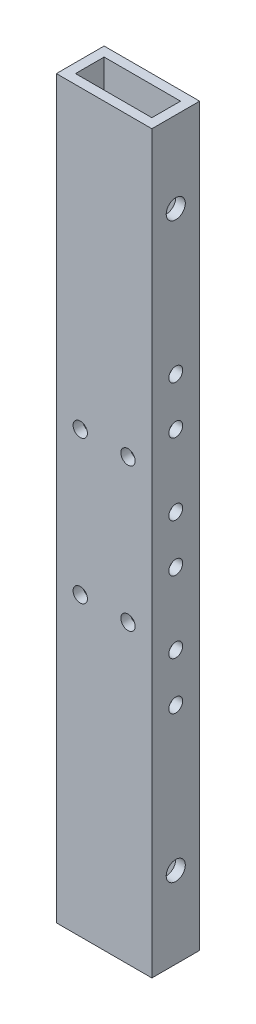
SolidWorks part; units mm, degrees
ref_plane "前视基准面" through (0, 0, 0) normal (0, 0, 1) x (1, 0, 0)
ref_plane "上视基准面" through (0, 0, 0) normal (0, 1, 0) x (1, 0, 0)
ref_plane "右视基准面" through (0, 0, 0) normal (1, 0, 0) x (0, 0, -1)
sketch "草图1" plane through (0, 0, 0) normal (0, 1, 0) x (1, 0, 0)
  line L1 (-10, 5) -> (10, 5)
  line L2 (-10, 5) -> (-10, -5)
  line L3 (-10, -5) -> (10, -5)
  line L4 (10, 5) -> (10, -5)
  line L5 (-10, 5) -> (10, -5) construction
  line L6 (-10, -5) -> (10, 5) construction
  line L7 (-8, 3) -> (8, 3)
  line L8 (-8, 3) -> (-8, -3)
  line L9 (-8, -3) -> (8, -3)
  line L10 (8, 3) -> (8, -3)
  line L11 (-8, 3) -> (8, -3) construction
  line L12 (-8, -3) -> (8, 3) construction
  point P0 (0, 0)
  point P6 (0, 0)
  dimension "D1" = 10
  dimension "D2" = 20
  dimension "D3" = 2
  dimension "D4" = 2
extrude "凸台-拉伸1" add sketch "草图1" along normal mid plane 154
sketch "草图2" plane through (10, 0, 0) normal (1, 0, 0) x (0, 0, -1)
  line L0 (0, 0) -> (0, -17.282) construction
  line L1 (0, 0) -> (-14.5337, 0) construction
  circle A0 centre (0, 5) radius 1.45
  circle A1 centre (0, 20) radius 1.45
  circle A2 centre (0, 30) radius 1.45
  circle A3 centre (0, -30) radius 1.45
  circle A4 centre (0, -20) radius 1.45
  circle A5 centre (0, -5) radius 1.45
  circle A6 centre (0, 60) radius 2
  circle A7 centre (0, -60) radius 2
  dimension "D4" = 2.9
  dimension "D5" = 4
  dimension "D1" = 5
  dimension "D2" = 10
  dimension "D3" = 15
  dimension "D6" = 30
extrude "切除-拉伸1" cut sketch "草图2" against normal through all
sketch "草图3" plane through (0, 0, -5) normal (0, 0, -1) x (-1, 0, 0)
  line L0 (225.7, -20) -> (-54.3, -20) construction
  line L1 (10, 77) -> (10, -77) construction
  line L2 (0, 0) -> (17.2852, 0) construction
  line L3 (5, -15) -> (-5, -15) construction
  circle A0 centre (5, -15) radius 1.5
  circle A1 centre (-5, -15) radius 1.5
  circle A2 centre (5, 15) radius 1.5
  circle A3 centre (-5, 15) radius 1.5
  dimension "D4" = 3
  dimension "D1" = 5
  dimension "D2" = 5
  dimension "D3" = 10
extrude "切除-拉伸2" cut sketch "草图3" against normal through all
